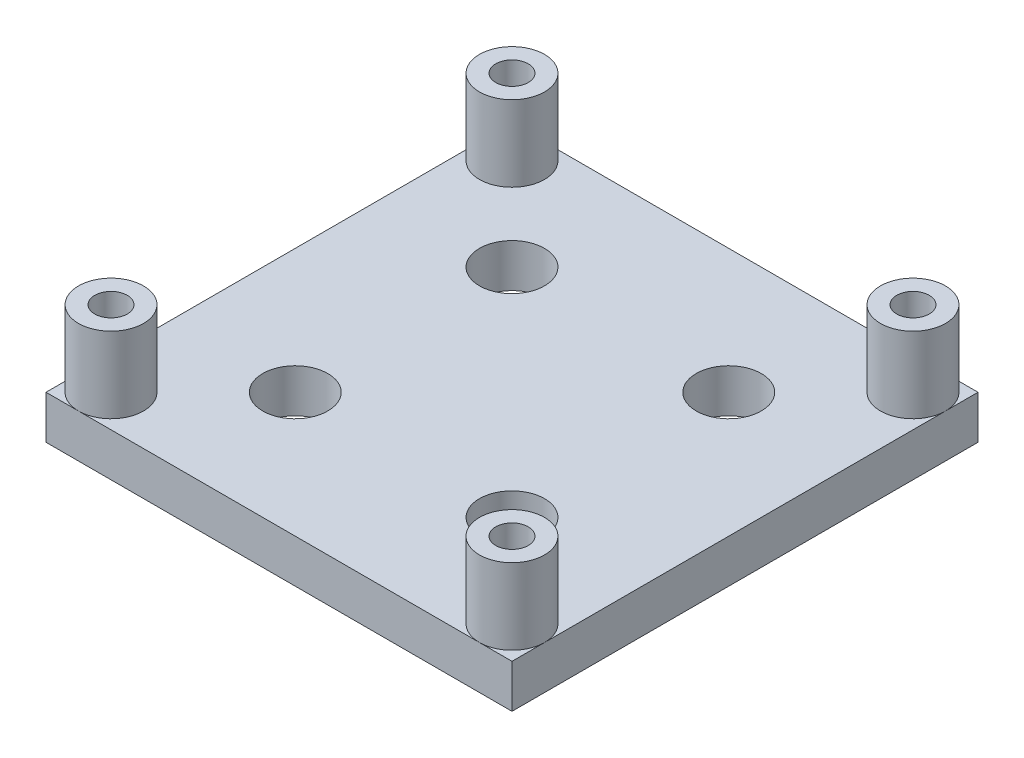
SolidWorks part; units mm, degrees
ref_plane "前视基准面" through (0, 0, 0) normal (0, 0, 1) x (1, 0, 0)
ref_plane "上视基准面" through (0, 0, 0) normal (0, 1, 0) x (1, 0, 0)
ref_plane "右视基准面" through (0, 0, 0) normal (1, 0, 0) x (0, 0, -1)
other "Configuration Table"
sketch "草图1" plane through (0, 0, 0) normal (0, 1, 0) x (1, 0, 0)
  line L0 (0, 0) -> (0, -50000) construction
  line L1 (-21.5, 21.5) -> (21.5, 21.5)
  line L2 (-21.5, 21.5) -> (-21.5, -21.5)
  line L3 (-21.5, -21.5) -> (21.5, -21.5)
  line L4 (21.5, 21.5) -> (21.5, -21.5)
  line L5 (-21.5, 21.5) -> (21.5, -21.5) construction
  line L6 (-21.5, -21.5) -> (21.5, 21.5) construction
  line L7 (-10, 44.6683) -> (-10, -49955.3317) construction
  line L8 (10, 41.0265) -> (10, -49958.9735) construction
  line L9 (-17.898, 10) -> (49982.102, 10) construction
  line L10 (-18.2291, -10) -> (49981.7709, -10) construction
  line L11 (-4.4091, 18.5) -> (49995.5909, 18.5) construction
  line L12 (18.5, 15.1184) -> (18.5, -49984.8816) construction
  line L13 (15.0588, -18.5) -> (-49984.9412, -18.5) construction
  line L14 (-18.5, -13.8599) -> (-18.5, -50013.8599) construction
  circle A0 centre (-10, 10) radius 3
  circle A1 centre (10, 10) radius 3
  circle A2 centre (-10, -10) radius 3
  circle A3 centre (10, -10) radius 3
  circle A4 centre (-18.5, 18.5) radius 1.5
  circle A5 centre (18.5, 18.5) radius 1.5
  circle A6 centre (18.5, -18.5) radius 1.5
  circle A7 centre (-18.5, -18.5) radius 1.5
  point P0 (0, 0)
  dimension "D7" = 6
  dimension "D8" = 6
  dimension "D9" = 6
  dimension "D10" = 6
  dimension "D13" = 3
  dimension "D16" = 3
  dimension "D17" = 3
  dimension "D18" = 3
  dimension "D1" = 43
  dimension "D2" = 43
  dimension "D3" = 10
  dimension "D4" = 10
  dimension "D5" = 10
  dimension "D6" = 10
  dimension "D11" = 3
  dimension "D12" = 3
  dimension "D14" = 3
  dimension "D15" = 3
extrude "凸台-拉伸1" add sketch "草图1" along normal blind 4
sketch "草图2" plane through (0, 4, 0) normal (0, 1, 0) x (1, 0, 0)
  circle A0 centre (-18.5, -18.5) radius 1.5
  circle A1 centre (-18.5, -18.5) radius 3
  circle A2 centre (18.5, -18.5) radius 1.5
  circle A3 centre (18.5, -18.5) radius 3
  circle A4 centre (18.5, 18.5) radius 1.5
  circle A5 centre (18.5, 18.5) radius 3
  circle A6 centre (-18.5, 18.5) radius 1.5
  circle A7 centre (-18.5, 18.5) radius 3
extrude "凸台-拉伸2" add sketch "草图2" along normal blind 7
